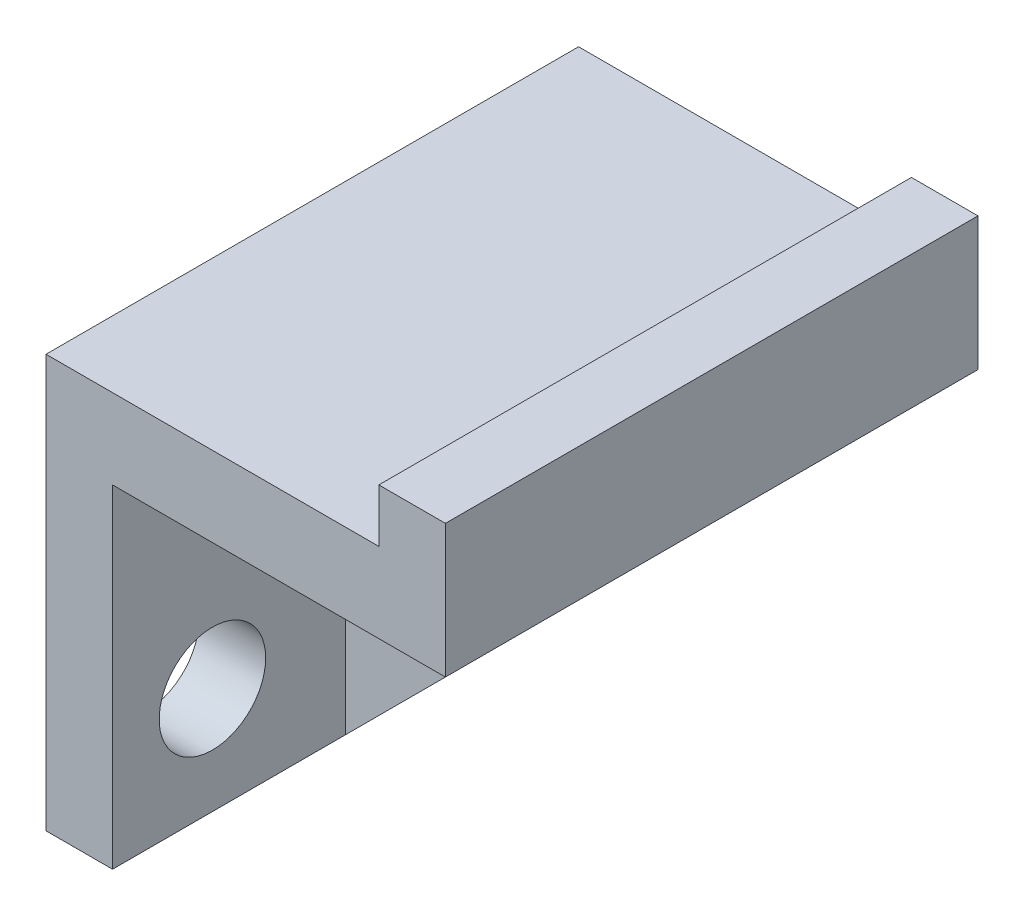
SolidWorks part; units mm, degrees
ref_plane "Front Plane" through (0, 0, 0) normal (0, 0, 1) x (1, 0, 0)
ref_plane "Top Plane" through (0, 0, 0) normal (0, 1, 0) x (1, 0, 0)
ref_plane "Right Plane" through (0, 0, 0) normal (1, 0, 0) x (0, 0, -1)
sketch "Sketch1" plane through (0, 0, 0) normal (0, 0, 1) x (1, 0, 0)
  line L0 (0, 0) -> (10000, 0)
  line L1 (10000, 0) -> (10000, 50000)
  line L2 (10000, 50000) -> (60000, 50000)
  line L3 (60000, 50000) -> (60000, 70000)
  line L4 (60000, 70000) -> (50000, 70000)
  line L5 (50000, 70000) -> (50000, 62000)
  line L6 (50000, 62000) -> (0, 62000)
  line L7 (0, 62000) -> (0, 0)
  dimension "D1" = 8000
  dimension "D2" = 10000
  dimension "D3" = 10000
  dimension "D4" = 70000
  dimension "D5" = 20000
  dimension "D6" = 50000
extrude "Boss-Extrude1" add sketch "Sketch1" along normal mid plane 80000
sketch "Sketch2" plane through (10000, 0, 0) normal (1, 0, 0) x (0, 0, -1)
  line L0 (-40000, 0) -> (-40000, 50000) construction
  line L1 (40000, 0) -> (40000, 50000) construction
  line L2 (-40000, 0) -> (40000, 0) construction
  circle A0 centre (-25000, 16000) radius 8000
  circle A1 centre (25000, 16000) radius 8000
  point P4 (23621.1674, 19982.5691)
  point P7 (-29827.9797, 20441.5233)
  dimension "D3" = 15000
  dimension "D5" = 16000
  dimension "D6" = 16000
  dimension "D1" = 50000
  dimension "D2" = 15000
  dimension "D4" = 16000
extrude "Cut-Extrude1" cut sketch "Sketch2" against normal through all
sketch "Sketch3" plane through (0, 0, 40000) normal (0, 0, 1) x (1, 0, 0)
  line L0 (60000, 50000) -> (10000, 50000)
  line L1 (10000, 50000) -> (10000, 0)
  line L2 (10000, 0) -> (60000, 50000)
extrude "Boss-Extrude2" add sketch "Sketch3" along normal blind 10000 from offset 45000
